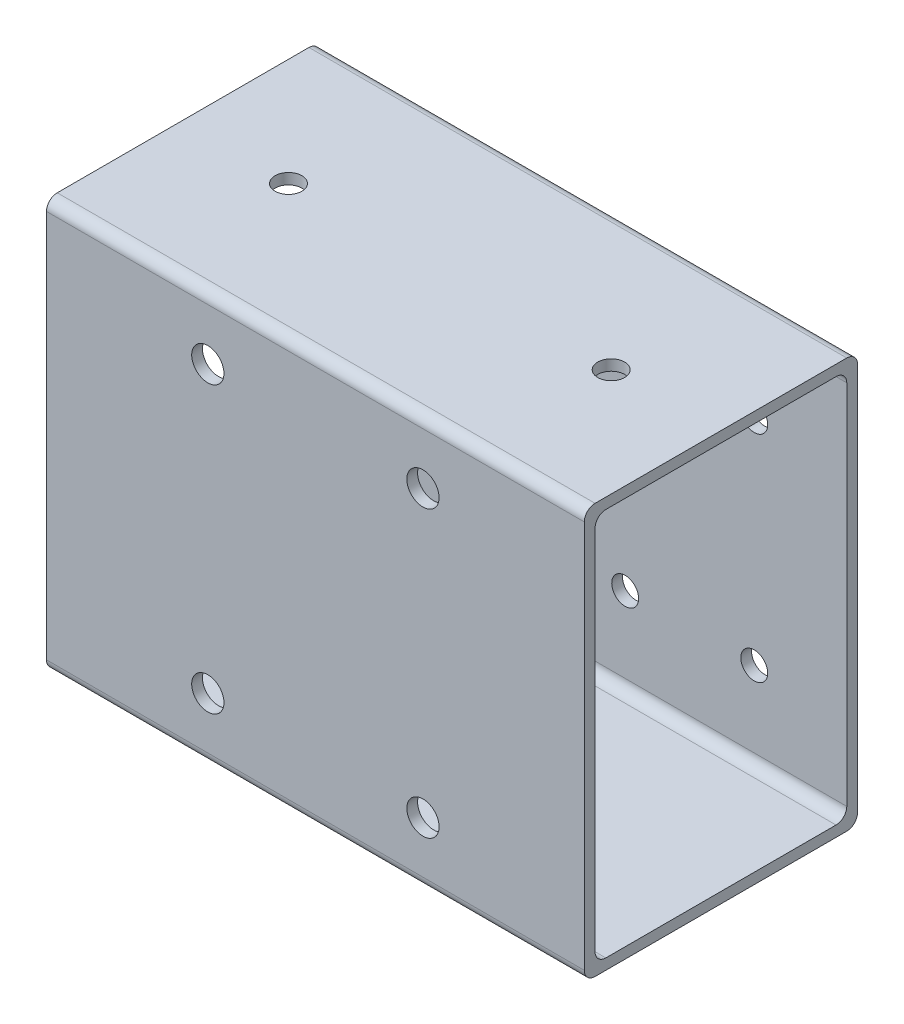
SolidWorks part; units mm, degrees
material "A500"
ref_plane "Alzado" through (0, 0, 0) normal (0, 0, 1) x (1, 0, 0)
ref_plane "Planta" through (0, 0, 0) normal (0, 1, 0) x (1, 0, 0)
ref_plane "Vista lateral" through (0, 0, 0) normal (1, 0, 0) x (0, 0, -1)
sketch "Sketch1" plane through (0, 0, 0) normal (1, 0, 0) x (0, 0, -1)
  line L1 (25.4, 38.1) -> (-25.4, 38.1)
  line L2 (25.4, 38.1) -> (25.4, -38.1)
  line L3 (25.4, -38.1) -> (-25.4, -38.1)
  line L4 (-25.4, 38.1) -> (-25.4, -38.1)
  line L5 (25.4, 38.1) -> (-25.4, -38.1) construction
  line L6 (25.4, -38.1) -> (-25.4, 38.1) construction
  point P0 (0, 0)
  dimension "D1" = 76.2
  dimension "D2" = 50.8
extrude "Boss-Extrude1" add sketch "Sketch1" against normal blind 100
sketch "Sketch2" plane through (0, 0, 0) normal (1, 0, 0) x (0, 0, -1)
  line L0 (25.4, 38.1) -> (-25.4, 38.1) construction
  line L1 (23.4, 36.1) -> (-23.4, 36.1)
  line L2 (23.4, 36.1) -> (23.4, -36.1)
  line L3 (23.4, -36.1) -> (-23.4, -36.1)
  line L4 (-23.4, 36.1) -> (-23.4, -36.1)
  line L5 (23.4, 36.1) -> (-23.4, -36.1) construction
  line L6 (23.4, -36.1) -> (-23.4, 36.1) construction
  line L7 (25.4, -38.1) -> (25.4, 38.1) construction
  point P0 (0, 0)
  dimension "D1" = 2
  dimension "D2" = 2
extrude "Cut-Extrude1" cut sketch "Sketch2" against normal through all
fillet "Fillet2" radius 2 8 edges at (-50, -38.1, -25.4) (-50, -38.1, 25.4) (-50, 38.1, 25.4) (-50, 38.1, -25.4) (-50, -36.1, -23.4) (-50, 36.1, -23.4) (-50, -36.1, 23.4) (-50, 36.1, 23.4)
sketch "Croquis2" plane through (0, 0, 25.4) normal (0, 0, 1) x (1, 0, 0)
  line L0 (-50, 36.1) -> (-50, -36.1) construction
  line L1 (0, 36.1) -> (-100, 36.1) construction
  line L2 (-100, -36.1) -> (0, -36.1) construction
  line L4 (-30, 26.5) -> (-70, 26.5)
  line L5 (-30, 26.5) -> (-30, -26.5)
  line L6 (-30, -26.5) -> (-70, -26.5)
  line L7 (-70, 26.5) -> (-70, -26.5)
  line L8 (-30, 26.5) -> (-70, -26.5) construction
  line L9 (-30, -26.5) -> (-70, 26.5) construction
  circle A0 centre (-70, 26.5) radius 3
  circle A1 centre (-30, 26.5) radius 3
  circle A2 centre (-30, -26.5) radius 3
  circle A3 centre (-70, -26.5) radius 3
  point P6 (-50, 0)
  dimension "D3" = 6
  dimension "D4" = 6
  dimension "D5" = 6
  dimension "D6" = 6
  dimension "D1" = 53
  dimension "D2" = 40
extrude "Cortar-Extruir2" cut sketch "Croquis2" against normal blind 10 contours L5 A1 L4 | L4 A1 L5 | L4 A0 L7 | L7 A0 L4 | L6 A3 L7 | L7 A3 L6 | L6 A2 L5 | L5 A2 L6
sketch "Croquis4" plane through (0, 0, -25.4) normal (0, 0, -1) x (-1, 0, 0)
  line L0 (49.2, 38.1) -> (49.2, -38.1) construction
  line L2 (0, 38.1) -> (100, 38.1) construction
  line L3 (100, -38.1) -> (0, -38.1) construction
  line L6 (100, -36.1) -> (100, 36.1) construction
  line L7 (100, 23.1) -> (49.2, 23.1) construction
  line L8 (100, -23.1) -> (49.2, -23.1) construction
  line L9 (49.2, 0) -> (100, 0) construction
  circle A1 centre (90, 23.1) radius 2.5
  circle A2 centre (59.2, 23.1) radius 2.5
  circle A3 centre (59.2, -23.1) radius 2.5
  circle A4 centre (90, -23.1) radius 2.5
  circle A5 centre (74.6, 0) radius 2.5
  dimension "D3" = 15
  dimension "D4" = 5
  dimension "D5" = 5
  dimension "D6" = 5
  dimension "D7" = 5
  dimension "D8" = 5
  dimension "D1" = 50.8
  dimension "D2" = 15
  dimension "D9" = 10
  dimension "D10" = 10
  dimension "D11" = 10
  dimension "D12" = 10
extrude "Cortar-Extruir5" cut sketch "Croquis4" against normal blind 10
sketch "Croquis6" plane through (0, 0, -25.4) normal (0, 0, -1) x (-1, 0, 0)
  line L0 (49.2, 38.1) -> (49.2, -38.1) construction
  line L8 (0, 0) -> (41.2, 0) construction
  line L9 (41.2, 20) -> (17.2, 20)
  line L10 (41.2, 20) -> (41.2, -20)
  line L11 (41.2, -20) -> (17.2, -20)
  line L12 (17.2, 20) -> (17.2, -20)
  line L13 (0, -36.1) -> (0, 36.1) construction
  line L14 (0, 38.1) -> (100, 38.1) construction
  line L15 (100, -38.1) -> (0, -38.1) construction
  line L16 (100, -36.1) -> (100, 36.1) construction
  circle A0 centre (17.2, 20) radius 2.5
  circle A1 centre (17.2, -20) radius 2.5
  circle A2 centre (41.2, -20) radius 2.5
  circle A3 centre (41.2, 20) radius 2.5
  dimension "D5" = 5
  dimension "D6" = 5
  dimension "D7" = 5
  dimension "D8" = 5
  dimension "D1" = 8
  dimension "D2" = 24
  dimension "D3" = 40
  dimension "D4" = 20
  dimension "D9" = 50.8
extrude "Cortar-Extruir6" cut sketch "Croquis6" against normal blind 10 contours A0 | A3 | A2 | A1
sketch "Croquis7" plane through (0, 38.1, 0) normal (0, 1, 0) x (1, 0, 0)
  line L0 (-100, -0.4) -> (0, -0.4) construction
  line L1 (-100, 23.4) -> (-100, -23.4) construction
  line L2 (0, 23.4) -> (0, -23.4) construction
  line L3 (0, -25.4) -> (-100, -25.4) construction
  circle A0 centre (-80, -0.4) radius 2.5
  circle A1 centre (-20, -0.4) radius 2.5
  dimension "D4" = 5
  dimension "D5" = 5
  dimension "D1" = 25
  dimension "D2" = 20
  dimension "D3" = 20
extrude "Cortar-Extruir7" cut sketch "Croquis7" against normal blind 10
